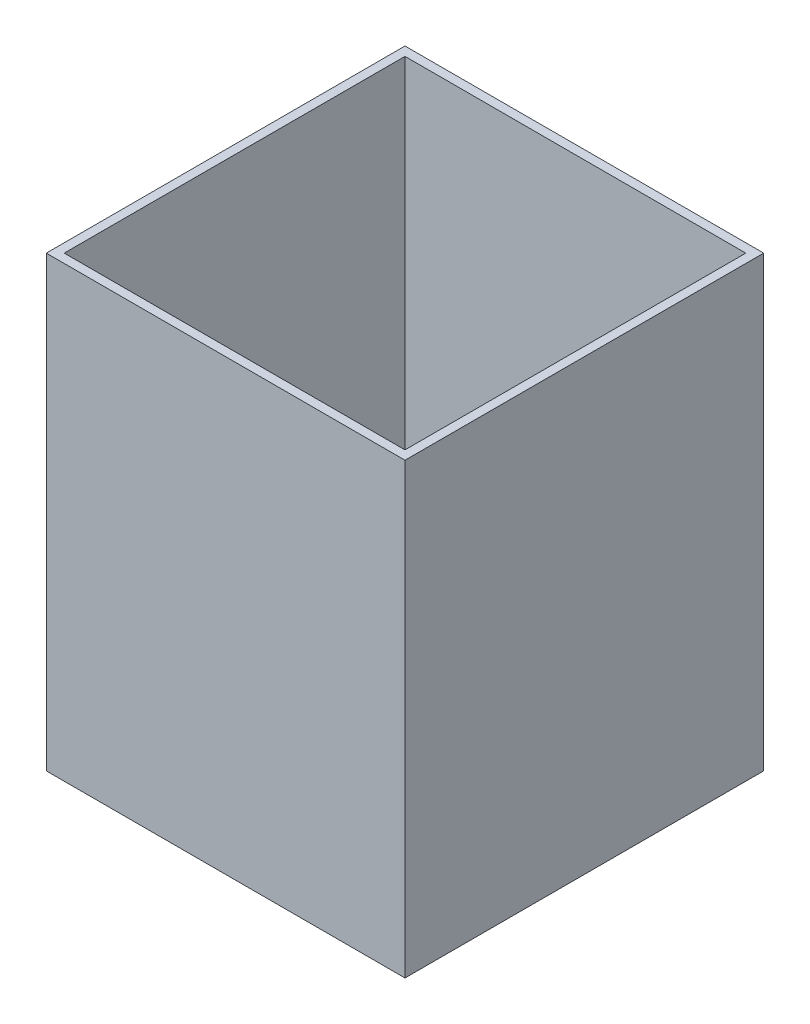
SolidWorks part; units mm, degrees
ref_plane "前视基准面" through (0, 0, 0) normal (0, 0, 1) x (1, 0, 0)
ref_plane "上视基准面" through (0, 0, 0) normal (0, 1, 0) x (1, 0, 0)
ref_plane "右视基准面" through (0, 0, 0) normal (1, 0, 0) x (0, 0, -1)
sketch "草图1" plane through (0, 0, 0) normal (0, 1, 0) x (1, 0, 0)
  line L0 (-48, 48) -> (-48, -28)
  line L1 (-50, 50) -> (30, 50)
  line L2 (-50, 50) -> (-50, -30)
  line L3 (-50, -30) -> (30, -30)
  line L4 (30, 50) -> (30, -30)
  line L5 (-48, -28) -> (28, -28)
  line L6 (28, 48) -> (28, -28)
  line L7 (-48, 48) -> (28, 48)
  point P4 (-10, 50)
  point P6 (30, 10)
  dimension "D1" = 80
  dimension "D2" = 2
extrude "凸台-拉伸1" add sketch "草图1" along normal mid plane 100
